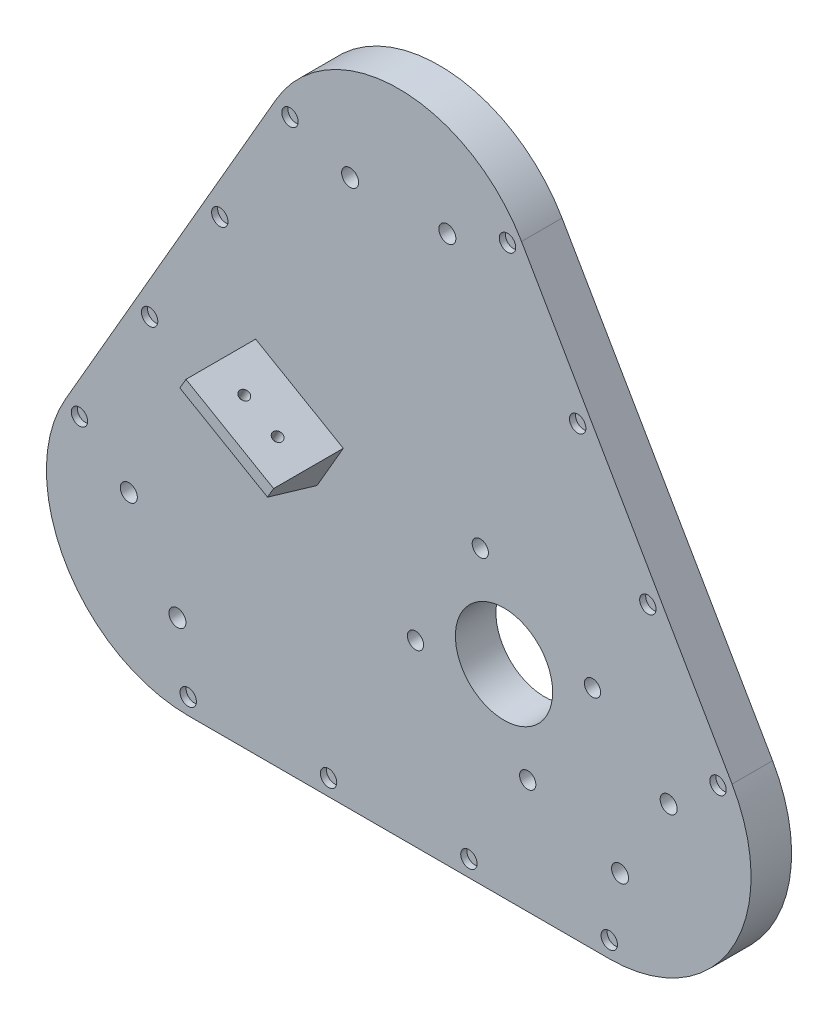
SolidWorks part; units mm, degrees
ref_plane "Plano frontal" through (0, 0, 0) normal (0, 0, 1) x (1, 0, 0)
ref_plane "Plano superior" through (0, 0, 0) normal (0, 1, 0) x (1, 0, 0)
ref_plane "Plano direito" through (0, 0, 0) normal (1, 0, 0) x (0, 0, -1)
sketch "Esboço1" plane through (0, 0, 0) normal (0, 0, 1) x (1, 0, 0)
  line L0 (0, 0) -> (0, 60) construction
  line L1 (0, 0) -> (-51.9615, -30) construction
  line L2 (0, 0) -> (51.9615, -30) construction
  line L3 (0, 0) -> (0, -52.5079) construction
  line L4 (0, 0) -> (45.4731, 26.2539) construction
  line L5 (0, 0) -> (-45.4731, 26.2539) construction
  line L6 (-12, 70) -> (12, 70) construction
  line L7 (-66.6218, -24.6077) -> (-54.6218, -45.3923) construction
  line L8 (-51.9615, -30) -> (-60.6218, -35) construction
  line L9 (0, 60) -> (0, 70) construction
  line L10 (51.9615, -30) -> (60.6218, -35) construction
  line L11 (54.6218, -45.3923) -> (66.6218, -24.6077) construction
  line L12 (31.8335, -36.8427) -> (39.8285, -22.995) construction
  line L13 (47.8235, -9.1473) -> (39.8285, -22.995) construction
  line L14 (-51.9615, -65) -> (51.9615, -65)
  line L15 (30.3109, 77.5) -> (82.2724, -12.5)
  line L16 (-30.3109, 77.5) -> (-82.2724, -12.5)
  arc A1 (51.9615, -65) -> (82.2724, -12.5) centre (51.9615, -30) ccw
  arc A2 (30.3109, 77.5) -> (-30.3109, 77.5) centre (0, 60) ccw
  arc A3 (-82.2724, -12.5) -> (-51.9615, -65) centre (-51.9615, -30) ccw
  circle A10 centre (-12, 70) radius 2.1
  circle A11 centre (-66.6218, -24.6077) radius 2.1
  circle A12 centre (12, 70) radius 2.1
  circle A13 centre (-54.6218, -45.3923) radius 2.1
  circle A24 centre (66.6218, -24.6077) radius 2.1
  circle A25 centre (54.6218, -45.3923) radius 2.1
  circle A26 centre (31.8335, -36.8427) radius 2
  circle A27 centre (25.9808, -15) radius 12
  circle A28 centre (4.138, -20.8527) radius 2
  circle A29 centre (20.128, 6.8427) radius 2
  circle A30 centre (47.8235, -9.1473) radius 2
  point P25 (0, 70)
  point P40 (51.9615, -30)
  point P41 (51.9615, -30)
  point P45 (60.6218, -35)
  point P53 (25.9808, -15)
  dimension "D3" = 24
  dimension "D5" = 70
  dimension "D9" = 4.2
  dimension "D10" = 12
  dimension "D11" = 12
  dimension "D12" = 10
  dimension "D13" = 70
  dimension "D14" = 30
  dimension "D15" = 4
  dimension "D16" = 15.99
  dimension "D17" = 10
  dimension "D18" = 24
  dimension "D19" = 4
  dimension "D1" = 120
  dimension "D2" = 120
  dimension "D4" = 60
  dimension "D6" = 120
  dimension "D7" = 120
extrude "Ressalto-extrusão1" add sketch "Esboço1" along normal blind 10
sketch "Esboço2" plane through (0, 0, 10) normal (0, 0, 1) x (1, 0, 0)
  line L0 (-56.2917, 32.5) -> (-26.005, 14.9581) construction
  line L1 (-30.3109, 77.5) -> (-82.2724, -12.5) construction
  line L2 (-36.8216, 21.2231) -> (-15.1883, 8.6932)
  line L3 (-15.1883, 8.6932) -> (-13.6847, 11.2892)
  line L4 (-13.6847, 11.2892) -> (-35.3181, 23.8191)
  line L5 (-35.3181, 23.8191) -> (-36.8216, 21.2231)
  point P7 (-26.005, 14.9581)
  dimension "D1" = 35
  dimension "D2" = 25
  dimension "D3" = 3
extrude "Ressalto-extrusão2" add sketch "Esboço2" along normal blind 17.2
sketch "Esboço3" plane through (-0.045, -0.0777, 0) normal (-0.5012, -0.8653, 0) x (0.8653, -0.5012, 0)
  line L0 (-29.9999, 27.2) -> (-29.9999, 10) construction
  line L1 (-42.4999, 27.2) -> (-17.4999, 27.2) construction
  line L2 (-42.4999, 10) -> (-17.4999, 10) construction
  line L3 (-34.7499, 19.5) -> (-25.2499, 19.5) construction
  circle A0 centre (-34.7499, 19.5) radius 1.2
  circle A1 centre (-25.2499, 19.5) radius 1.2
  point P4 (-29.9999, 19.5)
  dimension "D1" = 2.4
  dimension "D2" = 9.5
  dimension "D3" = 7.7
extrude "Corte-extrusão1" cut sketch "Esboço3" against normal up to surface (3 mm away) up to face at (-24.5014, 17.5541, 18.6)
sketch "Esboço4" plane through (-36.7766, 21.3008, 0) normal (-0.8653, 0.5012, 0) x (0, 0, 1)
  line L0 (27.2, -0.0898) -> (5.5494, -12.5898)
  line L1 (27.2, -0.0898) -> (10, -0.0898) construction
  dimension "D1" = 30
  dimension "D2" = 25
rib "Nervura1" sketch "Esboço4" sketch "Esboço4" thickness 2.5 extrusion direction parallel to sketch draft on no parameters "D1"=2.5
ref_plane "Plano1" through (-25.96, 15.0359, 0) normal (-0.8653, 0.5012, 0) x (0, 0, 1)
mirror "Espelhar1" about plane through (-25.96, 15.0359, 0) normal (-0.8653, 0.5012, 0) of "Nervura1"
sketch "Esboço5" plane through (0, 0, 10) normal (0, 0, 1) x (1, 0, 0)
  line L3 (-30.3109, 77.5) -> (-82.2724, -12.5)
  line L4 (-51.9615, -65) -> (51.9615, -65)
  line L5 (82.2724, -12.5) -> (30.3109, 77.5)
  line L6 (-30.3109, 77.5) -> (-82.2724, -12.5) construction
  line L7 (-51.9615, -65) -> (51.9615, -65) construction
  line L8 (82.2724, -12.5) -> (30.3109, 77.5) construction
  line L12 (-26.8468, 75.5) -> (-78.8083, -14.5) construction
  line L13 (-51.9615, -61) -> (51.9615, -61) construction
  line L14 (78.8083, -14.5) -> (26.8468, 75.5) construction
  arc A3 (30.3109, 77.5) -> (-30.3109, 77.5) centre (0, 60) ccw
  arc A4 (-82.2724, -12.5) -> (-51.9615, -65) centre (-51.9615, -30) ccw
  arc A5 (51.9615, -65) -> (82.2724, -12.5) centre (51.9615, -30) ccw
  arc A6 (30.3109, 77.5) -> (-30.3109, 77.5) centre (0, 60) ccw construction
  arc A7 (-82.2724, -12.5) -> (-51.9615, -65) centre (-51.9615, -30) ccw construction
  arc A8 (51.9615, -65) -> (82.2724, -12.5) centre (51.9615, -30) ccw construction
  arc A25 (26.8468, 75.5) -> (-26.8468, 75.5) centre (0, 60) ccw construction
  arc A26 (-78.8083, -14.5) -> (-51.9615, -61) centre (-51.9615, -30) ccw construction
  arc A27 (51.9615, -61) -> (78.8083, -14.5) centre (51.9615, -30) ccw construction
  circle A28 centre (-78.8083, -14.5) radius 2.025
  circle A29 centre (-51.9615, -61) radius 2.025
  circle A30 centre (26.8468, 75.5) radius 2.025
  circle A31 centre (44.1668, 45.5009) radius 2.025
  circle A32 centre (61.4868, 15.5018) radius 2.025
  circle A33 centre (78.8068, -14.4974) radius 2.025
  circle A34 centre (-61.4883, 15.4991) radius 2.025
  circle A35 centre (-44.1683, 45.4982) radius 2.025
  circle A36 centre (-26.8483, 75.4974) radius 2.025
  circle A37 centre (-17.3215, -61) radius 2.025
  circle A38 centre (17.3185, -61) radius 2.025
  circle A39 centre (51.9585, -61) radius 2.025
  dimension "D3" = 103.923
  dimension "D2" = 4.05
  dimension "D4" = 4
  dimension "D8" = 4
  dimension "D1" = 0
  dimension "D5" = 4
  dimension "D6" = 4
extrude "Corte-extrusão2" cut sketch "Esboço5" against normal blind 1.5
